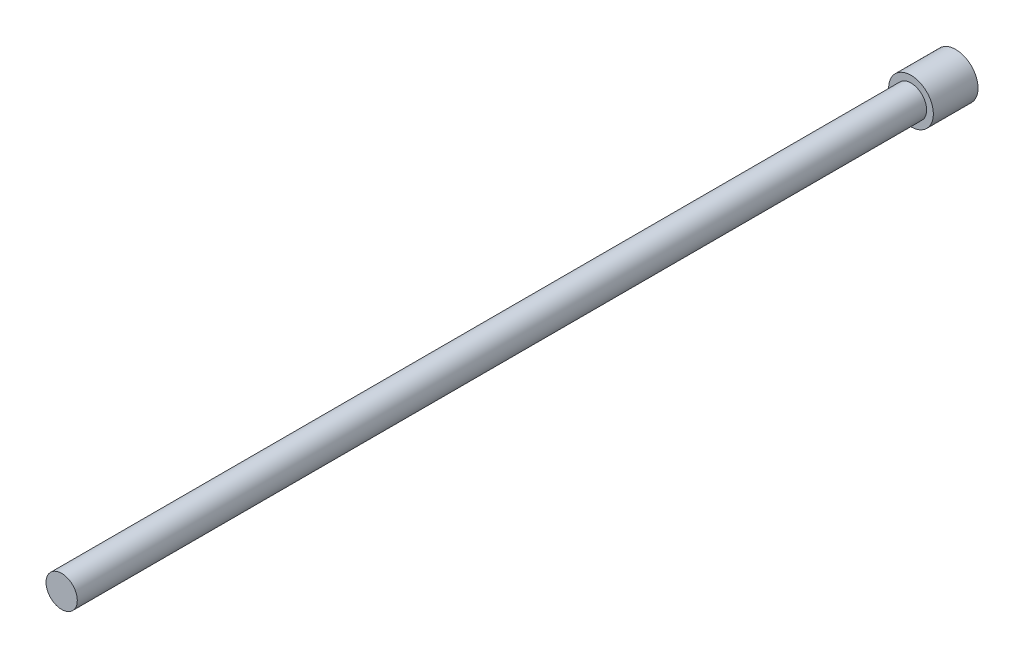
SolidWorks part; units mm, degrees
ref_plane "前视基准面" through (0, 0, 0) normal (0, 0, 1) x (1, 0, 0)
ref_plane "上视基准面" through (0, 0, 0) normal (0, 1, 0) x (1, 0, 0)
ref_plane "右视基准面" through (0, 0, 0) normal (1, 0, 0) x (0, 0, -1)
sketch "草图1" plane through (0, 0, 0) normal (0, 0, 1) x (1, 0, 0)
  circle A0 centre (0, 0) radius 3.5
  dimension "D1" = 7
extrude "凸台-拉伸1" add sketch "草图1" along normal blind 200
sketch "草图2" plane through (0, 0, 0) normal (0, 0, -1) x (-1, 0, 0)
  circle A0 centre (0, 0) radius 5
  dimension "D1" = 10
extrude "凸台-拉伸2" add sketch "草图2" against normal blind 10
